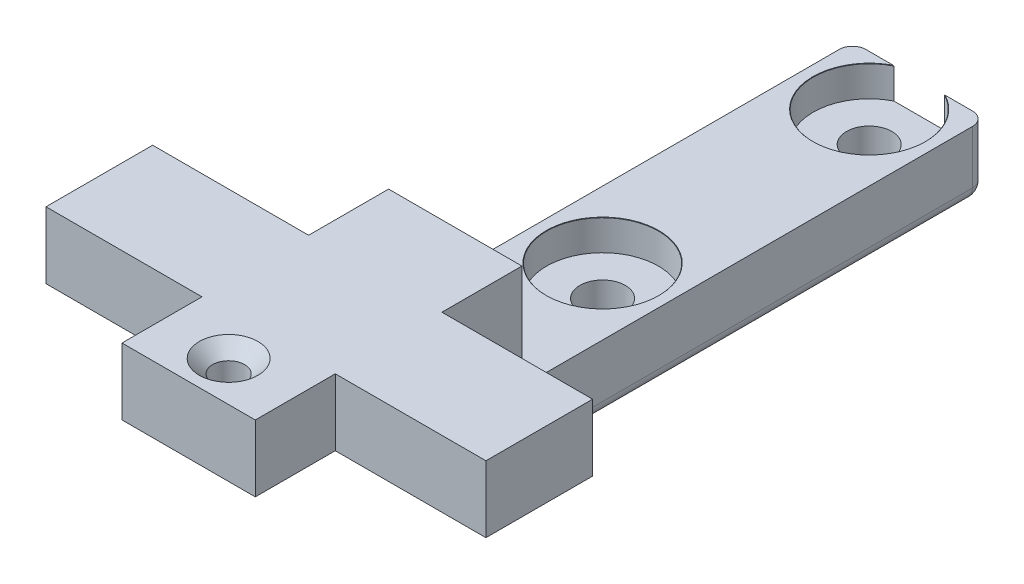
SolidWorks part; units mm, degrees
material "PF"
ref_plane "Front Plane" through (0, 0, 0) normal (0, 0, 1) x (1, 0, 0)
ref_plane "Top Plane" through (0, 0, 0) normal (0, 1, 0) x (1, 0, 0)
ref_plane "Right Plane" through (0, 0, 0) normal (1, 0, 0) x (0, 0, -1)
sketch "Sketch1" plane through (0, 0, 0) normal (0, 1, 0) x (1, 0, 0)
  line L1 (0, 44.9638) -> (10, 44.9638)
  line L2 (0, 44.9638) -> (0, 4.1638)
  line L3 (0, 4.1638) -> (10, 4.1638)
  line L4 (10, 44.9638) -> (10, 4.1638)
  line L9 (20.3, 4.1638) -> (-10.7, 4.1638) construction
  line L11 (-14.4321, 44.9638) -> (10.4679, 44.9638) construction
  circle A0 centre (5, 41.2138) radius 1.7 construction
  dimension "D1" = 10
  dimension "D3" = 5
extrude "Boss-Extrude1" add sketch "Sketch1" along normal blind 5
sketch "Sketch7" plane through (0, 5, 0) normal (0, 1, 0) x (1, 0, 0)
  line L0 (0, 44.9638) -> (0, 4.1638) construction
  line L1 (10, 4.1638) -> (0, 4.1638)
  line L2 (10, 4.1638) -> (10, 10.1638)
  line L3 (10, 10.1638) -> (0, 10.1638)
  line L4 (0, 4.1638) -> (0, 10.1638)
  dimension "D1" = 6
extrude "Boss-Extrude2" add sketch "Sketch7" along normal blind 7.83
sketch "Sketch8" plane through (0, 0, -4.1638) normal (0, 0, 1) x (1, 0, 0)
  line L0 (0, 12.83) -> (10, 12.83) construction
  line L1 (21.3, 12.83) -> (-11.7, 12.83)
  line L2 (21.3, 12.83) -> (21.3, 7.83)
  line L3 (21.3, 7.83) -> (-11.7, 7.83)
  line L4 (-11.7, 12.83) -> (-11.7, 7.83)
  dimension "D1" = 5
extrude "Boss-Extrude3" add sketch "Sketch8" along normal blind 8
sketch "Sketch9" plane through (0, 0, 3.8362) normal (0, 0, 1) x (1, 0, 0)
  line L0 (-11.7, 7.83) -> (21.3, 7.83) construction
  line L1 (0, 7.83) -> (10, 7.83)
  line L2 (0, 7.83) -> (0, 12.83)
  line L3 (0, 12.83) -> (10, 12.83)
  line L4 (10, 7.83) -> (10, 12.83)
  line L5 (21.3, 12.83) -> (-11.7, 12.83) construction
  line L6 (0, 7.83) -> (0, 0) construction
  line L7 (10, 7.83) -> (10, 0) construction
extrude "Boss-Extrude4" add sketch "Sketch9" along normal blind 6
hole_wizard "CSK for M2 Flat Head Machine Screw1" positions "Sketch10" profile "Sketch11" countersink size "M2" standard "ANSI Metric" end condition through all
sketch "Sketch10" plane through (0, 12.83, 0) normal (0, 1, 0) x (1, 0, 0)
  line L2 (5, -6.8362) -> (0, -6.8362) construction
  line L7 (5, -6.8362) -> (10, -6.8362) construction
  line L8 (10, -9.8362) -> (10, -3.8362) construction
  line L9 (0, -9.8362) -> (0, -3.8362) construction
  line L10 (10, -9.8362) -> (0, -9.8362) construction
  point P0 (5, -6.8362)
  dimension "D1" = 3
sketch "Sketch11" plane through (5, 12.83, 6.8362) normal (1, 0, 0) x (0, 0, 1)
  line L0 (0, 0) -> (0, 12.83)
  line L1 (0, 12.83) -> (1.2, 12.83)
  line L2 (1.2, 12.83) -> (1.2, 1)
  line L3 (1.2, 1) -> (2.2, 0)
  line L5 (2.2, 0) -> (0, 0)
  line L6 (-1.2, 1) -> (-2.2, 0) construction
  line L11 (0, -6.35) -> (0, 107.95) construction
  dimension "Thru Hole Dia." = 2.4
  dimension "Thru Hole Depth" = 12.83
  dimension "Near C'Sink Dia." = 4.4
  dimension "Near C'Sink Angle" = 90
hole_wizard "CBORE for M3 Hex Head Machine Screw1" positions "Sketch12" profile "Sketch13" counterbore size "M3" standard "ANSI Metric" end condition through all
sketch "Sketch12" plane through (0, 5, 0) normal (0, 1, 0) x (1, 0, 0)
  line L0 (5, 21.2138) -> (10, 21.2138) construction
  line L1 (10, 10.1638) -> (10, 44.9638) construction
  line L3 (5, 21.2138) -> (0, 21.2138) construction
  line L4 (0, 44.9638) -> (0, 10.1638) construction
  line L6 (5, 21.2138) -> (5, 41.2138) construction
  line L8 (10, 44.9638) -> (0, 44.9638) construction
  point P0 (5, 21.2138)
  point P2 (5, 41.2138)
  dimension "D1" = 20
  dimension "D2" = 3.75
sketch "Sketch13" plane through (5, 5, -21.2138) normal (1, 0, 0) x (0, 0, 1)
  line L0 (0, 0) -> (0, 5)
  line L1 (0, 5) -> (1.7, 5)
  line L3 (1.7, 5) -> (1.7, 2.3)
  line L4 (4.2, 2.3) -> (1.7, 2.3)
  line L5 (4.2, 2.3) -> (4.2, 0.025)
  line L6 (4.2, 0.025) -> (4.225, 0)
  line L7 (4.225, 0) -> (0, 0)
  line L8 (-4.2, 0.025) -> (-4.225, 0) construction
  line L11 (0, -6.35) -> (0, 107.95) construction
  dimension "Thru Hole Dia." = 3.4
  dimension "Thru Hole Depth" = 5
  dimension "C'Bore Dia." = 8.4
  dimension "C'Bore Depth" = 2.3
  dimension "Near C'Sink Dia." = 8.45
  dimension "Near C'Sink Angle" = 90
fillet "Fillet1" radius 1 7 edges at (5, 7.83, -4.1638) (5, 0, -4.1638) (10, 0, -24.5638) (0, 2.5, -44.9638) (0, 0, -24.5638) (10, 2.5, -44.9638) (5, 0, -44.9638)
